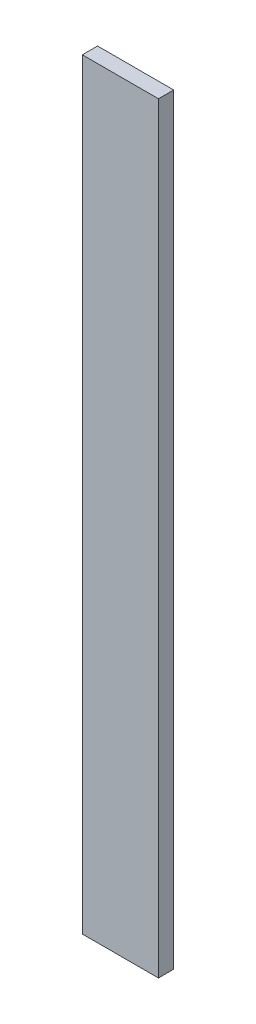
SolidWorks part; units mm, degrees
ref_plane "Front Plane" through (0, 0, 0) normal (0, 0, 1) x (1, 0, 0)
ref_plane "Top Plane" through (0, 0, 0) normal (0, 1, 0) x (1, 0, 0)
ref_plane "Right Plane" through (0, 0, 0) normal (1, 0, 0) x (0, 0, -1)
sketch "Sketch1" plane through (0, 0, 0) normal (0, 1, 0) x (1, 0, 0)
  line L1 (-25, -5) -> (25, -5)
  line L2 (-25, -5) -> (-25, 5)
  line L3 (-25, 5) -> (25, 5)
  line L4 (25, -5) -> (25, 5)
  line L5 (-25, -5) -> (25, 5) construction
  line L6 (-25, 5) -> (25, -5) construction
  point P0 (0, 0)
  dimension "D1" = 10
  dimension "D2" = 50
extrude "Boss-Extrude1" add sketch "Sketch1" along normal blind 500
